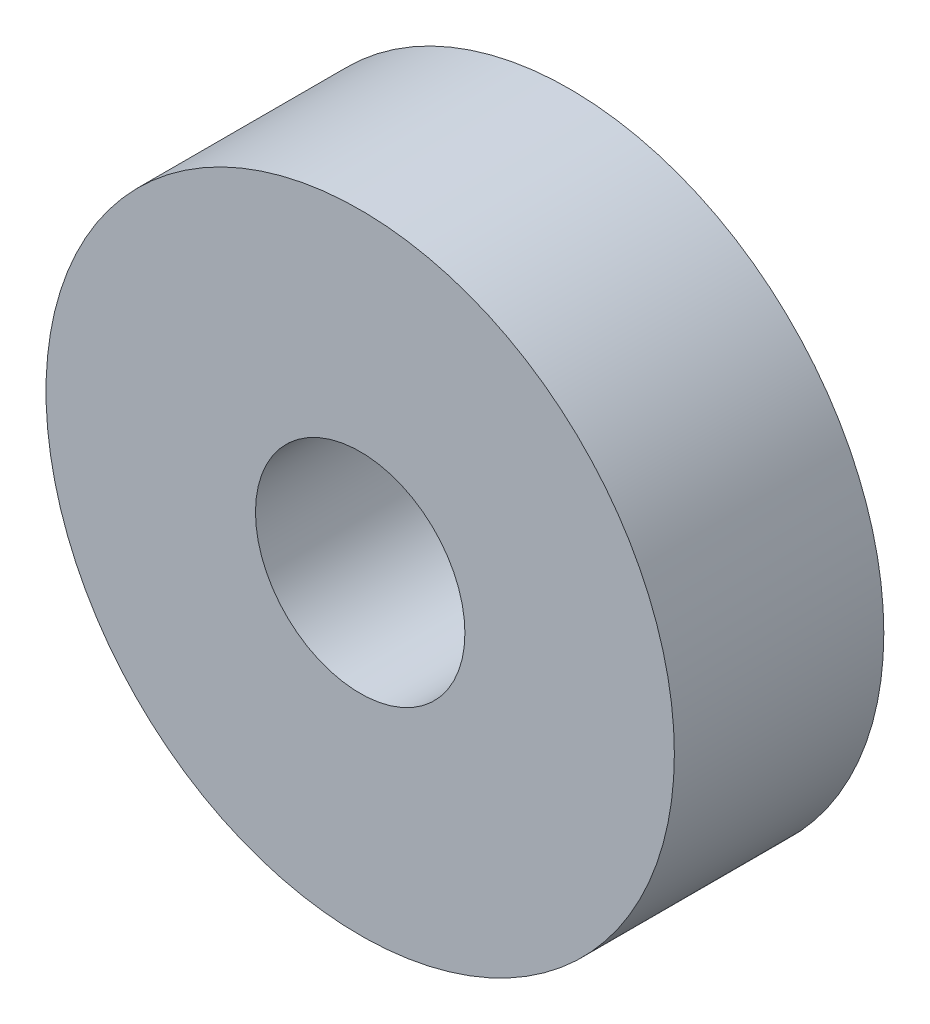
SolidWorks part; units mm, degrees
ref_plane "前视基准面" through (0, 0, 0) normal (0, 0, 1) x (1, 0, 0)
ref_plane "上视基准面" through (0, 0, 0) normal (0, 1, 0) x (1, 0, 0)
ref_plane "右视基准面" through (0, 0, 0) normal (1, 0, 0) x (0, 0, -1)
sketch "草图1" plane through (0, 0, 0) normal (0, 0, 1) x (1, 0, 0)
  circle A0 centre (0, 0) radius 2
  circle A1 centre (0, 0) radius 6
  dimension "D1" = 4
  dimension "D2" = 12
extrude "凸台-拉伸1" add sketch "草图1" along normal blind 4
